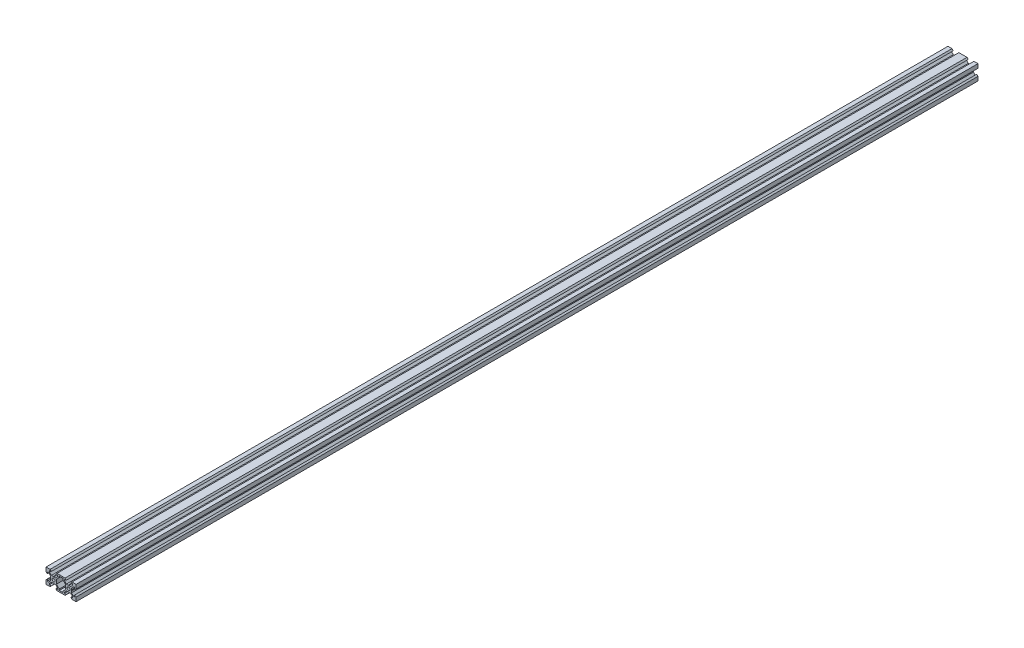
SolidWorks part; units mm, degrees
ref_plane "Front Plane" through (0, 0, 0) normal (0, 0, 1) x (1, 0, 0)
ref_plane "Top Plane" through (0, 0, 0) normal (0, 1, 0) x (1, 0, 0)
ref_plane "Right Plane" through (0, 0, 0) normal (1, 0, 0) x (0, 0, -1)
sketch "Sketch1" plane through (0, 0, 0) normal (0, 0, 1) x (1, 0, 0)
  line L0 (-5.3896, 10) -> (5.3896, 10)
  line L1 (0, 10) -> (0, 4.6104) construction
  line L2 (-6.1, -2.8393) -> (-2.3769, -6.5562)
  line L3 (5.3896, -10) -> (-5.3896, -10) construction
  line L5 (-6.1, 2.8393) -> (-6.1, -2.8393)
  line L6 (-4.5, 8.2) -> (-4.5, 6.5562)
  line L7 (2.3832, 6.5562) -> (2.3832, 8.2)
  line L9 (-6.1, 2.8393) -> (-2.3832, 6.5562)
  line L10 (-4.5, 6.5562) -> (-7.1607, 3.9)
  line L11 (-2.3832, 6.5562) -> (-2.3832, 8.2)
  line L12 (-5.3896, 10) -> (-6.9, 8.2)
  line L13 (6.1, 2.8393) -> (2.3832, 6.5562)
  line L14 (-6.9, 8.2) -> (-4.5, 8.2)
  line L15 (-16.5562, 5.5) -> (-18.2, 5.5)
  line L16 (0, 0) -> (6.1, 0) construction
  line L17 (-6.9, -8.2) -> (-4.5, -8.2)
  line L18 (-2.3769, -6.5562) -> (-2.3769, -8.2)
  line L19 (-5.3896, -10) -> (-6.9, -8.2)
  line L20 (2.3769, -6.5562) -> (2.3769, -8.2)
  line L21 (-9.4804, -3.9002) -> (-10, -3.6002)
  line L22 (-9.4804, 3.8998) -> (-10, 3.5998)
  line L23 (6.1, -2.8393) -> (2.3769, -6.5562)
  line L24 (-2.3769, -8.2) -> (2.3769, -8.2)
  line L25 (-2.3832, 8.2) -> (2.3832, 8.2)
  line L26 (-9.4804, 3.8998) -> (-7.1607, 3.9)
  line L27 (-5.3896, -10) -> (5.3896, -10)
  line L28 (-9.4804, -3.9002) -> (-7.1604, -3.9002)
  line L29 (-4.5, -6.5562) -> (-7.1607, -3.9)
  line L30 (-20, 10) -> (20, 10) construction
  line L32 (6.1, 2.8393) -> (6.1, -2.8393)
  line L33 (-4.5, -8.2) -> (-4.5, -6.5562)
  line L34 (-16.5562, -5.5) -> (-18.2, -5.5)
  line L36 (-10, 0) -> (-10, 8.2) construction
  line L37 (-20, -10) -> (-14.6104, -10) construction
  line L38 (-20, -10) -> (-20, -4.6104) construction
  line L39 (-20, 10) -> (-20, 4.6104) construction
  line L40 (-20, 10) -> (-14.6104, 10) construction
  line L41 (-20, -10) -> (-20, -4.6104)
  line L42 (-15.5, -8.2) -> (-15.5, -6.5562)
  line L43 (-20, -10) -> (-14.6104, -10)
  line L44 (7.1519, 3.8998) -> (9.4804, 3.8998)
  line L45 (-16.5562, -5.5) -> (-13.9, -2.8393)
  line L46 (-15.5, -6.5562) -> (-12.8393, -3.9)
  line L47 (-12.8393, -3.9) -> (-10.5196, -3.9002)
  line L48 (-13.9, -2.8393) -> (-13.9, -0.5196)
  line L49 (-12.8393, 3.9) -> (-10.5196, 3.8998)
  line L50 (-13.9, 0.5196) -> (-13.9, 2.8393)
  line L51 (-13.9, 0.5196) -> (-13.6, 0)
  line L52 (-13.6, 0) -> (-13.9, -0.5196)
  line L53 (-10.5196, 3.8998) -> (-10, 3.5998)
  line L54 (-10.5196, -3.9002) -> (-10, -3.6002)
  line L55 (-20, -4.6104) -> (-18.2, -3.1)
  line L56 (-14.6104, -10) -> (-13.1, -8.2)
  line L57 (-18.2, -3.1) -> (-18.2, -5.5)
  line L58 (-13.1, -8.2) -> (-15.5, -8.2)
  line L59 (-20, -10) -> (20, -10) construction
  line L60 (-20, -10) -> (-20, 10) construction
  line L61 (-13.1, 8.2) -> (-15.5, 8.2)
  line L62 (-18.2, 3.1) -> (-18.2, 5.5)
  line L63 (-14.6104, 10) -> (-13.1, 8.2)
  line L64 (-20, 4.6104) -> (-18.2, 3.1)
  line L65 (-15.5, 6.5562) -> (-12.8393, 3.9)
  line L66 (-16.5562, 5.5) -> (-13.9, 2.8393)
  line L67 (-20, 10) -> (-20, 4.6104)
  line L68 (-20, 10) -> (-14.6104, 10)
  line L69 (-15.5, 8.2) -> (-15.5, 6.5562)
  line L70 (4.5, 6.5562) -> (7.1519, 3.8998)
  line L71 (15.5, 6.5562) -> (12.8481, 3.8998)
  line L72 (0, -10) -> (0, 10) construction
  line L73 (-20, -10) -> (0, 10) construction
  line L74 (10.5196, 3.8998) -> (12.8481, 3.8998)
  line L75 (12.8393, -3.9) -> (10.5192, -3.9)
  line L76 (20, -10) -> (0, 10) construction
  line L77 (20, -10) -> (20, 10) construction
  line L78 (20, 10) -> (14.6104, 10) construction
  line L79 (20, 10) -> (20, 4.6104) construction
  line L80 (20, -10) -> (20, -4.6104) construction
  line L81 (20, -10) -> (14.6104, -10) construction
  line L82 (10, 0) -> (10, 8.2) construction
  line L83 (20, 10) -> (20, 4.6104)
  line L84 (15.5, 8.2) -> (15.5, 6.5562)
  line L85 (20, 10) -> (14.6104, 10)
  line L87 (16.5562, 5.5) -> (13.9, 2.8393)
  line L89 (20, 4.6104) -> (18.2, 3.1)
  line L90 (14.6104, 10) -> (13.1, 8.2)
  line L91 (18.2, 3.1) -> (18.2, 5.5)
  line L92 (13.1, 8.2) -> (15.5, 8.2)
  line L93 (13.1, -8.2) -> (15.5, -8.2)
  line L94 (18.2, -3.1) -> (18.2, -5.5)
  line L95 (14.6104, -10) -> (13.1, -8.2)
  line L96 (20, -4.6104) -> (18.2, -3.1)
  line L97 (10.5196, -3.9002) -> (10, -3.6002)
  line L98 (10.5196, 3.8998) -> (10, 3.5998)
  line L99 (13.6, 0) -> (13.9, -0.5196)
  line L100 (13.9, 0.5196) -> (13.6, 0)
  line L101 (13.9, 0.5196) -> (13.9, 2.8393)
  line L102 (9.4808, -3.9) -> (7.1607, -3.9)
  line L103 (13.9, -2.8393) -> (13.9, -0.5196)
  line L105 (15.5, -6.5562) -> (12.8393, -3.9)
  line L106 (16.5562, -5.5) -> (13.9, -2.8393)
  line L107 (20, -10) -> (20, -4.6104)
  line L108 (20, -10) -> (14.6104, -10)
  line L109 (15.5, -8.2) -> (15.5, -6.5562)
  line L111 (16.5562, -5.5) -> (18.2, -5.5)
  line L112 (4.5, -8.2) -> (4.5, -6.5562)
  line L114 (4.5, -6.5562) -> (7.1607, -3.9)
  line L121 (9.4804, 3.8998) -> (10, 3.5998)
  line L122 (9.4804, -3.9002) -> (10, -3.6002)
  line L124 (5.3896, -10) -> (6.9, -8.2)
  line L126 (6.9, -8.2) -> (4.5, -8.2)
  line L128 (16.5562, 5.5) -> (18.2, 5.5)
  line L129 (6.9, 8.2) -> (4.5, 8.2)
  line L131 (5.3896, 10) -> (6.9, 8.2)
  line L135 (4.5, 8.2) -> (4.5, 6.5562)
  circle A0 centre (-10, 0) radius 2
  circle A1 centre (10, 0) radius 2
  dimension "D14" = 4
  dimension "D1" = 20
  dimension "D2" = 5.3896
  dimension "D3" = 1.8
  dimension "D4" = 1.5104
  dimension "D5" = 4.5
  dimension "D6" = 5.5
  dimension "D7" = 120
  dimension "D8" = 0.3
  dimension "D9" = 2.3197
  dimension "D10" = 7.8
  dimension "D11" = 20
  dimension "D12" = 1.5
  dimension "D13" = 2.6607
  dimension "D15" = 50
  dimension "D16" = 1.5
  dimension "D17" = 1.8
  dimension "D18" = 16.4
  dimension "D19" = 2.3832
  dimension "D20" = 45
extrude "Boss-Extrude1" add sketch "Sketch1" along normal blind 1200
